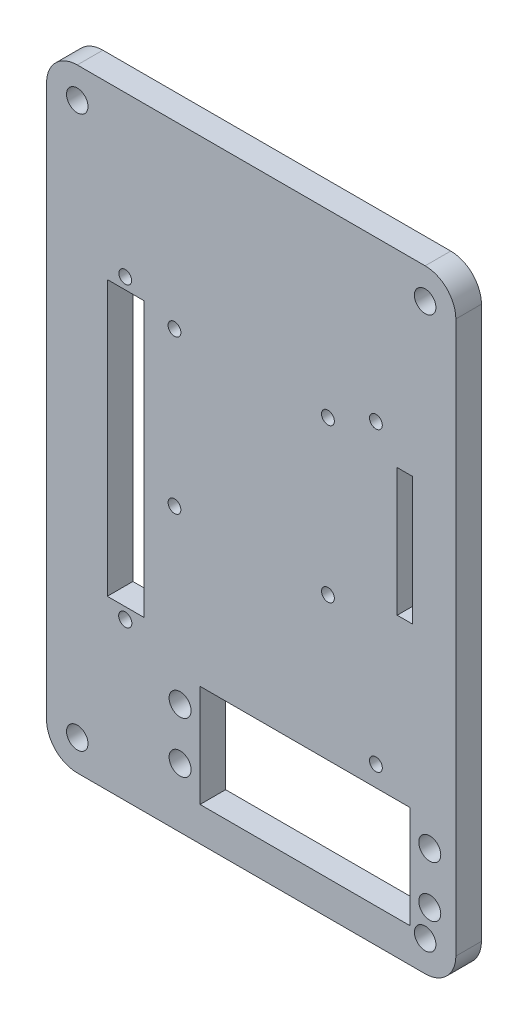
SolidWorks part; units mm, degrees
ref_plane "Ön Düzlem" through (0, 0, 0) normal (0, 0, 1) x (1, 0, 0)
ref_plane "Üst Düzlem" through (0, 0, 0) normal (0, 1, 0) x (1, 0, 0)
ref_plane "Sağ Düzlem" through (0, 0, 0) normal (1, 0, 0) x (0, 0, -1)
sketch "Çizim1" plane through (0, 0, 0) normal (0, 0, 1) x (1, 0, 0)
  line L1 (-31.3329, 55.3691) -> (48.6671, 55.3691)
  line L2 (-31.3329, 55.3691) -> (-31.3329, -44.6309)
  line L3 (-31.3329, -44.6309) -> (48.6671, -44.6309)
  line L4 (48.6671, 55.3691) -> (48.6671, -44.6309)
  dimension "D1" = 100
  dimension "D2" = 80
extrude "Yükseklik-Ekstrüzyon1" add sketch "Çizim1" along normal blind 5
sketch "Çizim2" plane through (0, 0, 0) normal (0, 0, -1) x (-1, 0, 0)
  line L0 (31.3329, 55.3691) -> (31.3329, -44.6309) construction
  line L1 (31.3329, -44.6309) -> (-48.6671, -44.6309) construction
  line L2 (-48.6671, 55.3691) -> (31.3329, 55.3691) construction
  line L3 (-48.6671, -44.6309) -> (-48.6671, 55.3691) construction
  circle A0 centre (15.9575, -33.8143) radius 1.2865
  circle A1 centre (-33.0425, -33.8143) radius 1.25
  circle A2 centre (-33.0425, 24.1857) radius 1.25
  circle A3 centre (15.9575, 24.1857) radius 1.25
  circle A4 centre (25.3329, -38.6309) radius 2.6236
  circle A5 centre (25.3329, 49.3691) radius 2.9399
  circle A6 centre (-42.6671, 49.3691) radius 2.812
  circle A7 centre (-42.6671, -38.6309) radius 2.8768
  dimension "D1" = 6
  dimension "D3" = 6
  dimension "D4" = 6
  dimension "D5" = 6
  dimension "D6" = 6
  dimension "D7" = 6
  dimension "D8" = 6
  dimension "D2" = 6
extrude "Kes-Ekstrüzyon1" cut sketch "Çizim2" against normal blind 10 contours A3 | A2 | A1 | A0
hole_wizard "M4 Helisarmal için Zıvana matkabı1" positions "3B Çizim1" profile "Çizim3" hole size "M4x0.7" standard "ANSI Metric" end condition up to next
sketch3d "3B Çizim1"
  point P0 (-25.3329, -38.6309, 0)
  point P3 (42.6671, -38.6309, 0)
  point P6 (-25.3329, 49.3691, 0)
  point P9 (42.6671, 49.3691, 0)
sketch "Çizim3" plane through (-25.3329, -38.6309, 0) normal (1, 0, 0) x (0, 1, 0)
  line L0 (0, 0) -> (0, 5)
  line L1 (0, 5) -> (2.1, 5)
  line L2 (2.1, 5) -> (2.1, 0)
  line L5 (2.1, 0) -> (0, 0)
  line L11 (0, -6.35) -> (0, 107.95) construction
  dimension "Thru Hole Dia." = 4.2
  dimension "Thru Hole Depth" = 5
fillet "Radyus1" radius 6 1 edges at (-31.3329, 55.3691, 2.5)
fillet "Radyus2" radius 6 1 edges at (-31.3329, -44.6309, 2.5)
fillet "Radyus3" radius 6 1 edges at (48.6671, -44.6309, 2.5)
fillet "Radyus4" radius 6 1 edges at (48.6671, 55.3691, 2.5)
sketch "Çizim4" plane through (0, 0, 5) normal (0, 0, 1) x (1, 0, 0)
  line L0 (27.6671, -11.3143) -> (27.6671, 21.6857)
  line L1 (27.6671, 21.6857) -> (40.2032, 21.6857)
  line L2 (40.2032, 21.6857) -> (40.2032, -10.8809)
  line L3 (40.2032, -10.8809) -> (27.6671, -11.3143)
  line L4 (40.2032, -6.5143) -> (37.2032, -6.5143)
  line L5 (37.2032, -6.5143) -> (37.2032, 18.4857)
  line L6 (37.2032, 18.4857) -> (40.2032, 18.4857)
  circle A0 centre (-6.3329, 20.1857) radius 1.25
  circle A1 centre (23.6671, 20.1857) radius 1.2558
  circle A2 centre (23.6671, -9.8143) radius 1.25
  circle A3 centre (-6.3329, -9.8143) radius 1.25
  dimension "D1" = 3
  dimension "D2" = 25
  dimension "D3" = 3.2
extrude "Kes-Ekstrüzyon2" cut sketch "Çizim4" against normal blind 50 contours L6 L5 L4 L2 | A2 | A1 | A0 | A3
sketch "Çizim5" plane through (0, 0, 0) normal (0, 0, -1) x (-1, 0, 0)
  line L0 (19.4575, 21.9827) -> (12.3329, 21.9827)
  line L1 (19.4575, 45.1857) -> (19.4575, -34.8143) construction
  line L4 (19.4575, -31.6348) -> (19.4575, 21.9827)
  line L8 (12.3329, -31.6348) -> (19.4575, -31.6348)
  line L9 (12.3329, -31.6348) -> (12.3329, 21.9827)
extrude "Kes-Ekstrüzyon3" cut sketch "Çizim5" against normal blind 50
sketch "Çizim6" plane through (0, 0, 5) normal (0, 0, 1) x (1, 0, 0)
  line L1 (-31.3329, -38.6309) -> (48.6671, -38.6309)
  line L2 (-31.3329, -38.6309) -> (-31.3329, -58.4829)
  line L3 (-25.3329, -64.4829) -> (42.6671, -64.4829)
  line L4 (48.6671, -38.6309) -> (48.6671, -58.4829)
  arc A0 (42.6671, -64.4829) -> (48.6671, -58.4829) centre (42.6671, -58.4829) ccw
  arc A1 (-31.3329, -58.4829) -> (-25.3329, -64.4829) centre (-25.3329, -58.4829) ccw
  circle A2 centre (-25.3329, -38.6309) radius 2.6
  circle A3 centre (42.6671, -38.6309) radius 2.6
  circle A4 centre (-5.2329, -52.8143) radius 2.15
  circle A5 centre (-5.2329, -42.8143) radius 2.15
  circle A6 centre (43.5671, -42.8143) radius 2.15
  circle A7 centre (43.5671, -52.8143) radius 2.15
  circle A8 centre (-25.3329, -58.4829) radius 2.1
  circle A9 centre (42.6671, -58.4829) radius 2.1
  circle A10 centre (42.6671, 49.3691) radius 2.1
  circle M15 centre (-25.3329, -38.6309) radius 2.1
  circle M16 centre (42.6671, -38.6309) radius 2.1
  arc M28 (-31.3329, -38.6309) -> (-25.3329, -44.6309) centre (-25.3329, -38.6309) ccw
  line M29 (-25.3329, -44.6309) -> (42.6671, -44.6309)
  arc M30 (42.6671, -44.6309) -> (48.6671, -38.6309) centre (42.6671, -38.6309) ccw
  dimension "D1" = 6
  dimension "D2" = 4.2
  dimension "D3" = 4.2
extrude "Yükseklik-Ekstrüzyon2" add sketch "Çizim6" against normal blind 5 contours A6 A5 L2 A1 L3 A0 L4 A9 A8 A7 A4 M30 M29 M28 | L1 M16 | A6 L1 M16 | L1 M15 | L1 M15
sketch "Çizim7" plane through (0, 0, 5) normal (0, 0, 1) x (1, 0, 0)
  circle A0 centre (43.5671, -42.8143) radius 2.15
  circle A1 centre (-5.2329, -42.8143) radius 2.15
extrude "Kes-Ekstrüzyon4" cut sketch "Çizim7" against normal blind 5
sketch "Çizim8" plane through (0, 0, 5) normal (0, 0, 1) x (1, 0, 0)
  line L0 (-1.3329, -38.6143) -> (-1.3329, -37.8143)
  line L2 (-1.3329, -37.8143) -> (39.6671, -37.8143)
  line L3 (-1.3329, -37.8143) -> (-1.3329, -57.8143)
  line L4 (-1.3329, -57.8143) -> (39.6671, -57.8143)
  line L5 (39.6671, -37.8143) -> (39.6671, -57.8143)
extrude "Kes-Ekstrüzyon5" cut sketch "Çizim8" against normal blind 5 contours L5 L2 L0 L3 L4
